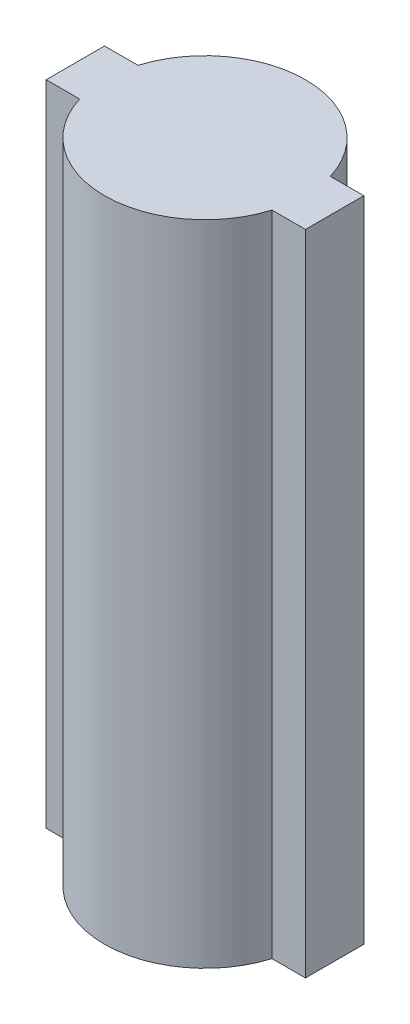
SolidWorks part; units mm, degrees
ref_plane "Front Plane" through (0, 0, 0) normal (0, 0, 1) x (1, 0, 0)
ref_plane "Top Plane" through (0, 0, 0) normal (0, 1, 0) x (1, 0, 0)
ref_plane "Right Plane" through (0, 0, 0) normal (1, 0, 0) x (0, 0, -1)
sketch "Sketch1" plane through (0, 0, 0) normal (0, 1, 0) x (1, 0, 0)
  line L1 (-4, 0.9) -> (4, 0.9)
  line L2 (-4, 0.9) -> (-4, -0.9)
  line L3 (-4, -0.9) -> (4, -0.9)
  line L4 (4, 0.9) -> (4, -0.9)
  line L5 (-4, 0.9) -> (4, -0.9) construction
  line L6 (-4, -0.9) -> (4, 0.9) construction
  circle A0 centre (0, 0) radius 3.1
  dimension "D1" = 6.2
  dimension "D2" = 1.8
  dimension "D3" = 8
extrude "Boss-Extrude1" add sketch "Sketch1" along normal blind 20 contours A0 L1 L2 L3 | A0 L3 L4 L1 | L3 A0 L1 | L3 A0 | L1 A0
